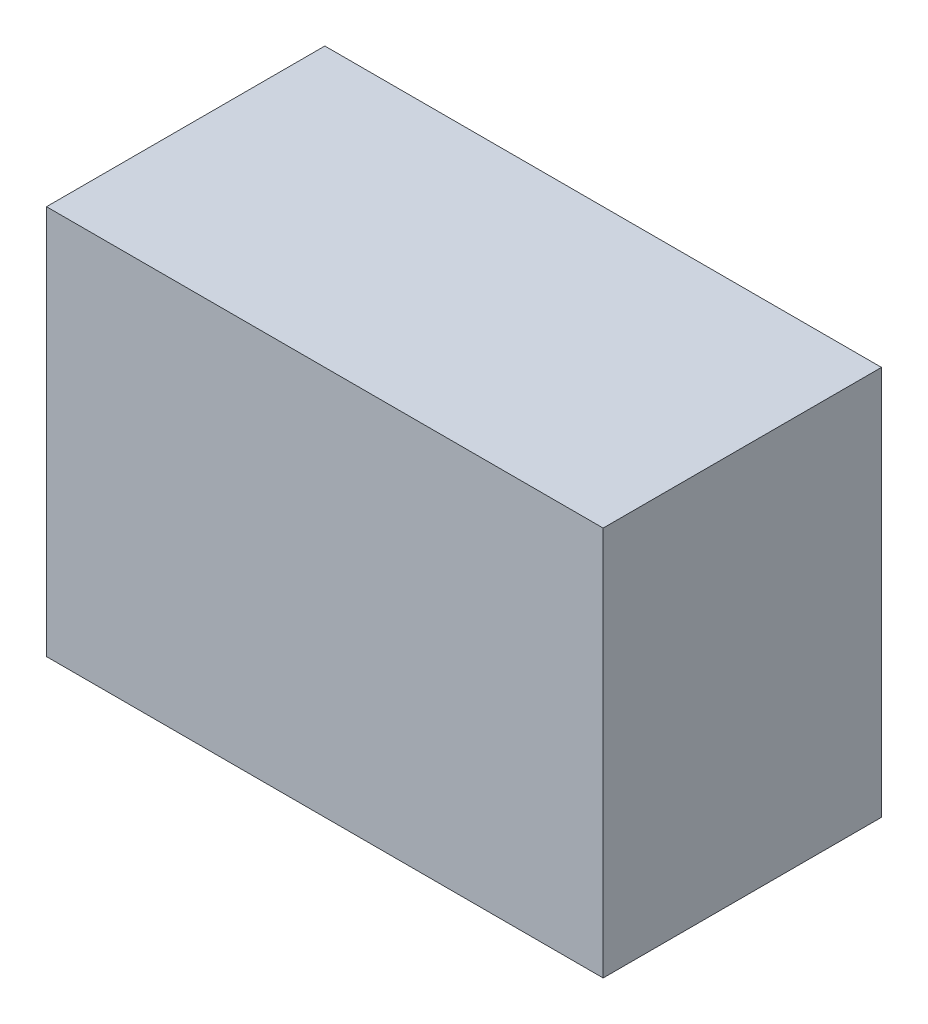
SolidWorks part; units mm, degrees
ref_plane "前视基准面" through (0, 0, 0) normal (0, 0, 1) x (1, 0, 0)
ref_plane "上视基准面" through (0, 0, 0) normal (0, 1, 0) x (1, 0, 0)
ref_plane "右视基准面" through (0, 0, 0) normal (1, 0, 0) x (0, 0, -1)
other "Configuration Table"
sketch "草图1" plane through (0, 0, 0) normal (0, 0, 1) x (1, 0, 0)
  line L1 (-50, -35) -> (50, -35)
  line L2 (-50, -35) -> (-50, 35)
  line L3 (-50, 35) -> (50, 35)
  line L4 (50, -35) -> (50, 35)
  line L5 (-50, -35) -> (50, 35) construction
  line L6 (-50, 35) -> (50, -35) construction
  point P0 (0, 0)
extrude "凸台-拉伸1" add sketch "草图1" along normal blind 50
